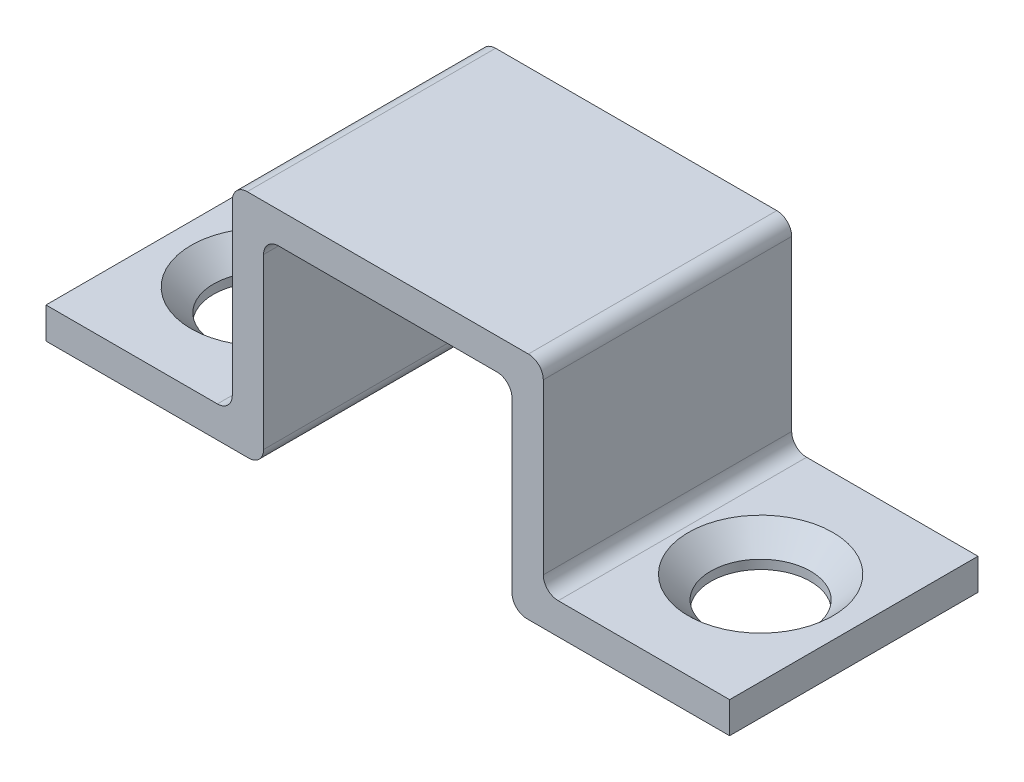
SolidWorks part; units mm, degrees
ref_plane "Front Plane" through (0, 0, 0) normal (0, 0, 1) x (1, 0, 0)
ref_plane "Top Plane" through (0, 0, 0) normal (0, 1, 0) x (1, 0, 0)
ref_plane "Right Plane" through (0, 0, 0) normal (1, 0, 0) x (0, 0, -1)
sketch "Sketch1" plane through (0, 0, 0) normal (0, 1, 0) x (1, 0, 0)
  line L1 (-6.35, -6.35) -> (6.35, -6.35)
  line L2 (-6.35, -6.35) -> (-6.35, 6.35)
  line L3 (-6.35, 6.35) -> (6.35, 6.35)
  line L4 (6.35, -6.35) -> (6.35, 6.35)
  line L5 (-6.35, -6.35) -> (6.35, 6.35) construction
  line L6 (-6.35, 6.35) -> (6.35, -6.35) construction
  point P0 (0, 0)
  dimension "D1" = 12.7
  dimension "D2" = 12.7
extrude "Boss-Extrude1" add sketch "Sketch1" along normal blind 1.6002
ref_plane "Plane1" through (6.35, 0, 0) normal (1, 0, 0) x (0, 0, -1)
sketch "Sketch2" plane through (6.35, 0, 0) normal (1, 0, 0) x (0, 0, -1)
  line L0 (6.35, 1.6002) -> (6.35, 0) construction
  line L1 (-6.35, 1.6002) -> (6.35, 1.6002)
  line L2 (-6.35, 1.6002) -> (-6.35, -10.16)
  line L3 (-6.35, -10.16) -> (6.35, -10.16)
  line L4 (6.35, 1.6002) -> (6.35, -10.16)
  line L5 (-6.35, 0) -> (6.35, 0) construction
  line L6 (-6.35, 0) -> (6.35, 0) construction
  dimension "D1" = 10.16
extrude "Boss-Extrude2" add sketch "Sketch2" along normal blind 1.6002
sketch "Sketch3" plane through (7.9502, 0, 0) normal (1, 0, 0) x (0, 0, -1)
  line L0 (6.35, -10.16) -> (6.35, 1.6002) construction
  line L1 (-6.35, -10.16) -> (6.35, -10.16)
  line L2 (-6.35, -10.16) -> (-6.35, -8.5598)
  line L3 (-6.35, -8.5598) -> (6.35, -8.5598)
  line L4 (6.35, -10.16) -> (6.35, -8.5598)
  dimension "D1" = 1.6002
extrude "Boss-Extrude3" add sketch "Sketch3" along normal blind 9.525
sketch "Sketch4" plane through (0, -8.5598, 0) normal (0, 1, 0) x (1, 0, 0)
  line L0 (12.7127, 6.35) -> (12.7127, -6.35) construction
  line L1 (17.4752, 6.35) -> (7.9502, 6.35) construction
  line L2 (17.4752, -6.35) -> (7.9502, -6.35) construction
  circle A0 centre (12.7127, 0) radius 2.5527
  dimension "D1" = 5.1054
extrude "Cut-Extrude1" cut sketch "Sketch4" against normal through all
mirror "Mirror2" about plane through (0, 0, 0) normal (1, 0, 0) of "Cut-Extrude1", "Boss-Extrude3", "Boss-Extrude2"
fillet "Fillet1" radius 0.762 8 edges at (6.35, -10.16, 0) (-6.35, -10.16, 0) (-7.9502, 1.6002, 0) (7.9502, 1.6002, 0)
chamfer "Chamfer2" distance 1.143 angle 45 2 edges at (-12.7127, -8.5598, 2.5527) (12.7127, -8.5598, 2.5527)
